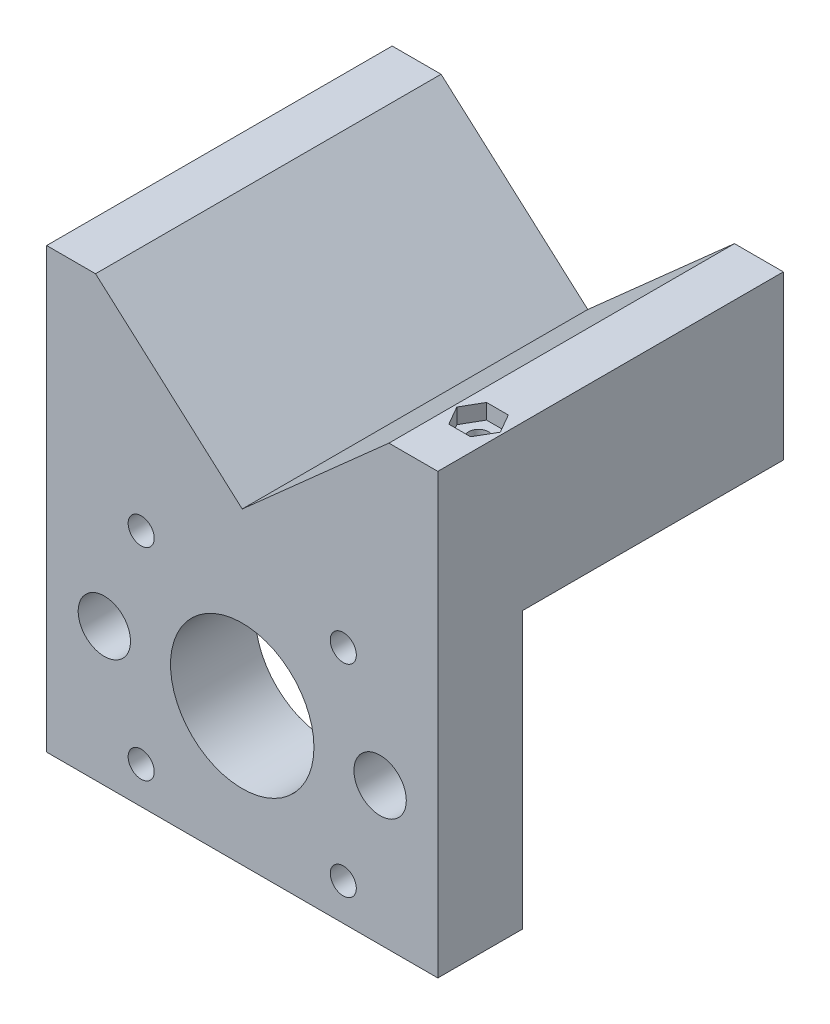
SolidWorks part; units mm, degrees
ref_plane "Front Plane" through (0, 0, 0) normal (0, 0, 1) x (1, 0, 0)
ref_plane "Top Plane" through (0, 0, 0) normal (0, 1, 0) x (1, 0, 0)
ref_plane "Right Plane" through (0, 0, 0) normal (1, 0, 0) x (0, 0, -1)
sketch "Sketch2" plane through (0, 0, 0) normal (0, 0, 1) x (1, 0, 0)
  line L1 (-21.0307, 18.2577) -> (38.9693, 18.2577)
  line L2 (-21.0307, 18.2577) -> (-21.0307, -24.0423)
  line L3 (-21.0307, -24.0423) -> (38.9693, -24.0423)
  line L4 (38.9693, 18.2577) -> (38.9693, -24.0423)
  dimension "D1" = 60
  dimension "D2" = 42.3
extrude "Boss-Extrude1" add sketch "Sketch2" against normal blind 13
sketch "Sketch4" plane through (0, 0, 0) normal (0, 0, 1) x (1, 0, 0)
  circle A0 centre (8.9693, -2.8923) radius 11
  circle A1 centre (24.4693, 12.6077) radius 2
  circle A2 centre (-6.5307, 12.6077) radius 2
  circle A3 centre (24.4693, -18.3923) radius 2
  circle A4 centre (-6.5307, -18.3923) radius 2
  dimension "D1" = 22
  dimension "D5" = 4
extrude "Cut-Extrude1" cut sketch "Sketch4" against normal through all
sketch "Sketch5" plane through (0, 0, 0) normal (0, 0, 1) x (1, 0, 0)
  circle A0 centre (30.1193, -2.8923) radius 4.015
  circle A1 centre (-12.1807, -2.8923) radius 4.015
  dimension "D2" = 8.03
extrude "Cut-Extrude2" cut sketch "Sketch5" against normal blind 10
sketch "Sketch6" plane through (0, 0, 0) normal (0, 0, 1) x (1, 0, 0)
  line L0 (-21.0307, 18.2577) -> (-21.0307, 43.2577)
  line L1 (38.9693, 18.2577) -> (38.9693, 43.2577)
  line L2 (-21.0307, 43.2577) -> (-13.5307, 43.2577)
  line L3 (38.9693, 43.2577) -> (31.4693, 43.2577)
  line L4 (-21.0307, 18.2577) -> (38.9693, 18.2577)
  line L5 (-13.5307, 43.2577) -> (8.9693, 23.2577)
  line L6 (31.4693, 43.2577) -> (8.9693, 23.2577)
  dimension "D1" = 25
  dimension "D2" = 25
  dimension "D3" = 7.5
  dimension "D4" = 7.5
extrude "Boss-Extrude2" add sketch "Sketch6" against normal blind 53
sketch "Sketch7" plane through (0, 43.2577, 0) normal (0, 1, 0) x (1, 0, 0)
  line L3 (38.5593, 10) -> (36.8893, 12.8925)
  line L4 (36.8893, 12.8925) -> (33.5493, 12.8925)
  line L5 (33.5493, 12.8925) -> (31.8793, 10)
  line L6 (31.8793, 10) -> (33.5493, 7.1075)
  line L7 (33.5493, 7.1075) -> (36.8893, 7.1075)
  line L8 (36.8893, 7.1075) -> (38.5593, 10)
  circle A0 centre (35.2193, 10) radius 2.8925 construction
  dimension "D2" = 3.34
extrude "Cut-Extrude3" cut sketch "Sketch7" against normal blind 2.35
sketch "Sketch8" plane through (0, 40.9077, 0) normal (0, 1, 0) x (1, 0, 0)
  circle A0 centre (35.2193, 10) radius 1.5
  dimension "D1" = 3
extrude "Cut-Extrude4" cut sketch "Sketch8" against normal blind 10
